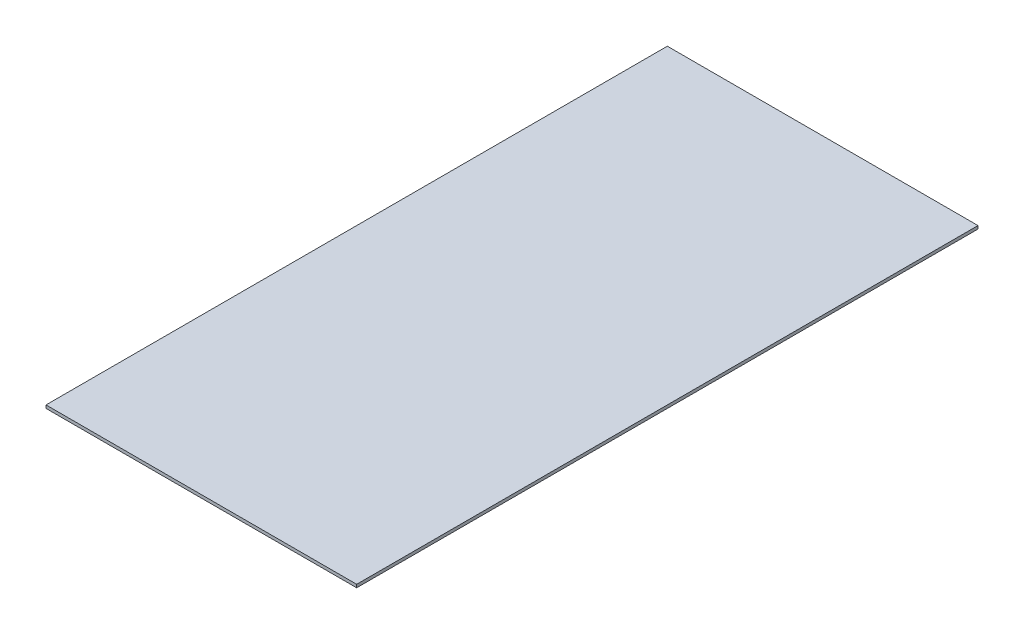
SolidWorks part; units mm, degrees
ref_plane "Front Plane" through (0, 0, 0) normal (0, 0, 1) x (1, 0, 0)
ref_plane "Top Plane" through (0, 0, 0) normal (0, 1, 0) x (1, 0, 0)
ref_plane "Right Plane" through (0, 0, 0) normal (1, 0, 0) x (0, 0, -1)
sketch "Sketch1" plane through (0, 0, 0) normal (0, 1, 0) x (1, 0, 0)
  line L1 (0, 0) -> (1219.2, 0)
  line L2 (0, 0) -> (0, 2438.4)
  line L3 (0, 2438.4) -> (1219.2, 2438.4)
  line L4 (1219.2, 0) -> (1219.2, 2438.4)
extrude "Boss-Extrude1" add sketch "Sketch1" along normal blind 12
sketch "Sketch2" plane through (0, 12, 0) normal (0, 1, 0) x (1, 0, 0)
  line L0 (0, 812.8) -> (1219.2, 812.8) construction
  line L4 (0, 0) -> (1219.2, 0) construction
  line L5 (0, 1625.6) -> (1219.2, 1625.6)
  line L6 (0, 2438.4) -> (0, 0) construction
  line L7 (1219.2, 0) -> (1219.2, 2438.4) construction
  line L8 (1219.2, 2438.4) -> (0, 2438.4) construction
  dimension "D1" = 812.8
  dimension "D2" = 812.8
  dimension "D3" = 812.8
